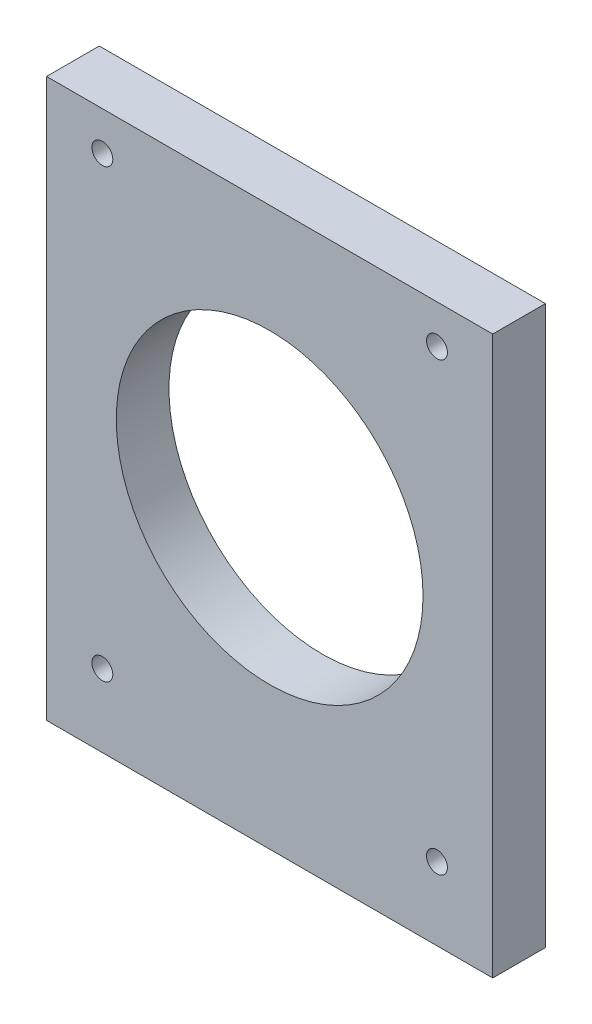
SolidWorks part; units mm, degrees
ref_plane "Front Plane" through (0, 0, 0) normal (0, 0, 1) x (1, 0, 0)
ref_plane "Top Plane" through (0, 0, 0) normal (0, 1, 0) x (1, 0, 0)
ref_plane "Right Plane" through (0, 0, 0) normal (1, 0, 0) x (0, 0, -1)
sketch "Sketch1" plane through (0, 0, 0) normal (0, 0, 1) x (1, 0, 0)
  line L1 (-56.666, 129.9221) -> (44.934, 129.9221)
  line L2 (-56.666, 129.9221) -> (-56.666, 2.9221)
  line L3 (-56.666, 2.9221) -> (44.934, 2.9221)
  line L4 (44.934, 129.9221) -> (44.934, 2.9221)
  line L5 (-43.966, 19.4971) -> (32.234, 19.4971) construction
  line L6 (-43.966, 19.4971) -> (-43.966, 121.0971) construction
  line L7 (-43.966, 121.0971) -> (32.234, 121.0971) construction
  line L8 (32.234, 19.4971) -> (32.234, 121.0971) construction
  line L9 (-43.966, 19.4971) -> (32.234, 121.0971) construction
  line L10 (-43.966, 121.0971) -> (32.234, 19.4971) construction
  circle A0 centre (-5.866, 70.2971) radius 34.925
  circle A1 centre (-43.966, 121.0971) radius 2.3812
  circle A2 centre (32.234, 121.0971) radius 2.3812
  circle A3 centre (-43.966, 19.4971) radius 2.3812
  circle A4 centre (32.234, 19.4971) radius 2.3812
  point P13 (32.234, 120.3058)
  point P15 (-43.3429, 19.4971)
  point P17 (32.234, 20.9197)
  dimension "D1" = 127
  dimension "D3" = 69.85
  dimension "D4" = 101.6
  dimension "D6" = 76.2
  dimension "D2" = 101.6
  dimension "D5" = 67.375
extrude "Boss-Extrude1" add sketch "Sketch1" along normal blind 12
